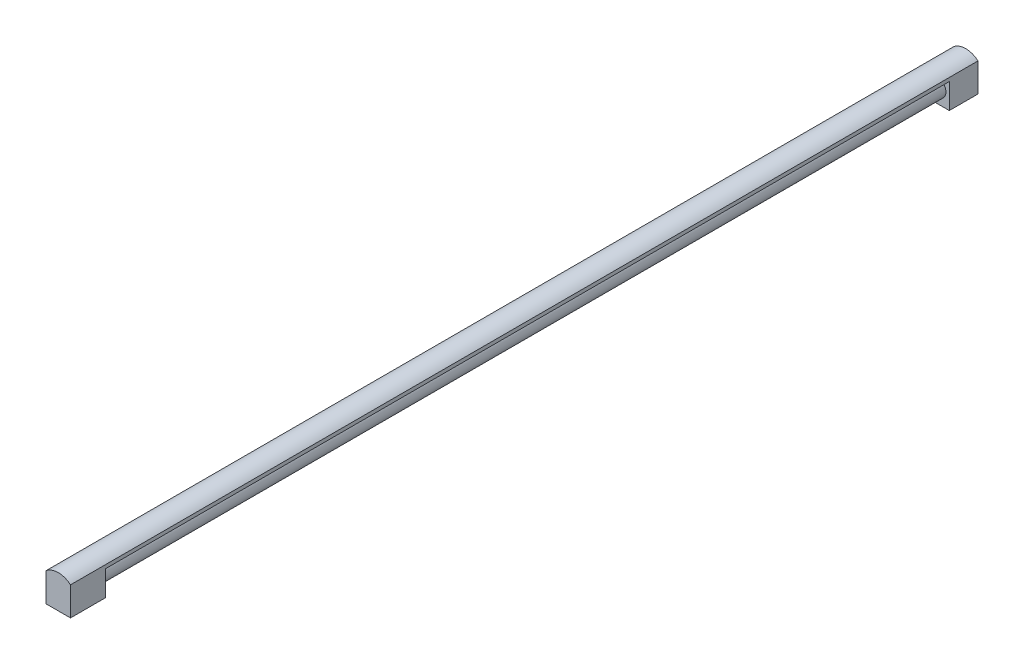
SolidWorks part; units mm, degrees
ref_plane "Front Plane" through (0, 0, 0) normal (0, 0, 1) x (1, 0, 0)
ref_plane "Top Plane" through (0, 0, 0) normal (0, 1, 0) x (1, 0, 0)
ref_plane "Right Plane" through (0, 0, 0) normal (1, 0, 0) x (0, 0, -1)
sketch "Sketch2" plane through (0, 0, 0) normal (0, 0, 1) x (1, 0, 0)
  line L1 (-17.5, -20.5) -> (17.5, -20.5)
  line L2 (-17.5, -20.5) -> (-17.5, 20.5)
  line L4 (17.5, -20.5) -> (17.5, 20.5)
  line L5 (-17.5, -20.5) -> (17.5, 20.5) construction
  line L6 (-17.5, 20.5) -> (17.5, -20.5) construction
  arc A0 (-17.5, 20.5) -> (17.5, 20.5) centre (0, 0) cw
  point P0 (0, 0)
  dimension "D1" = 41
  dimension "D2" = 35
extrude "Boss-Extrude1" add sketch "Sketch2" along normal blind 50
sketch "Sketch3" plane through (0, 0, 0) normal (0, 0, -1) x (-1, 0, 0)
  line L0 (-17.5, 20.5) -> (-17.5, 15.42)
  line L1 (-17.5, -20.5) -> (-17.5, 20.5) construction
  line L2 (-17.5, 15.42) -> (17.5, 15.42)
  line L3 (17.5, 20.5) -> (17.5, -20.5) construction
  line L4 (17.5, 15.42) -> (17.5, 20.5)
  circle A0 centre (0, 0) radius 12.7
  arc A1 (-17.5, 20.5) -> (17.5, 20.5) centre (0, 0) cw
  arc M2 (17.5, 20.5) -> (-17.5, 20.5) centre (0, 0) ccw
  line M3 (-17.5, 20.5) -> (-17.5, -20.5)
  line M5 (17.5, -20.5) -> (17.5, 20.5)
  dimension "D1" = 25.4
  dimension "D2" = 5.08
extrude "Boss-Extrude2" add sketch "Sketch3" along normal blind 1206 contours A0 | L2 M3 M5 M2
sketch "Sketch4" plane through (0, 0, -1206) normal (0, 0, -1) x (-1, 0, 0)
  line L2 (-17.5, 20.5) -> (-17.5, -20.5)
  line L3 (-17.5, -20.5) -> (17.5, -20.5)
  line L4 (17.5, 20.5) -> (17.5, -20.5)
  line L5 (-17.5, 20.5) -> (17.5, -20.5) construction
  line L6 (-17.5, -20.5) -> (17.5, 20.5) construction
  arc A0 (-17.5, 20.5) -> (17.5, 20.5) centre (0, 0) cw
  arc A1 (17.5, 20.5) -> (-17.5, 20.5) centre (0, 0) ccw construction
  point P0 (0, 0)
extrude "Boss-Extrude3" add sketch "Sketch4" along normal blind 41
